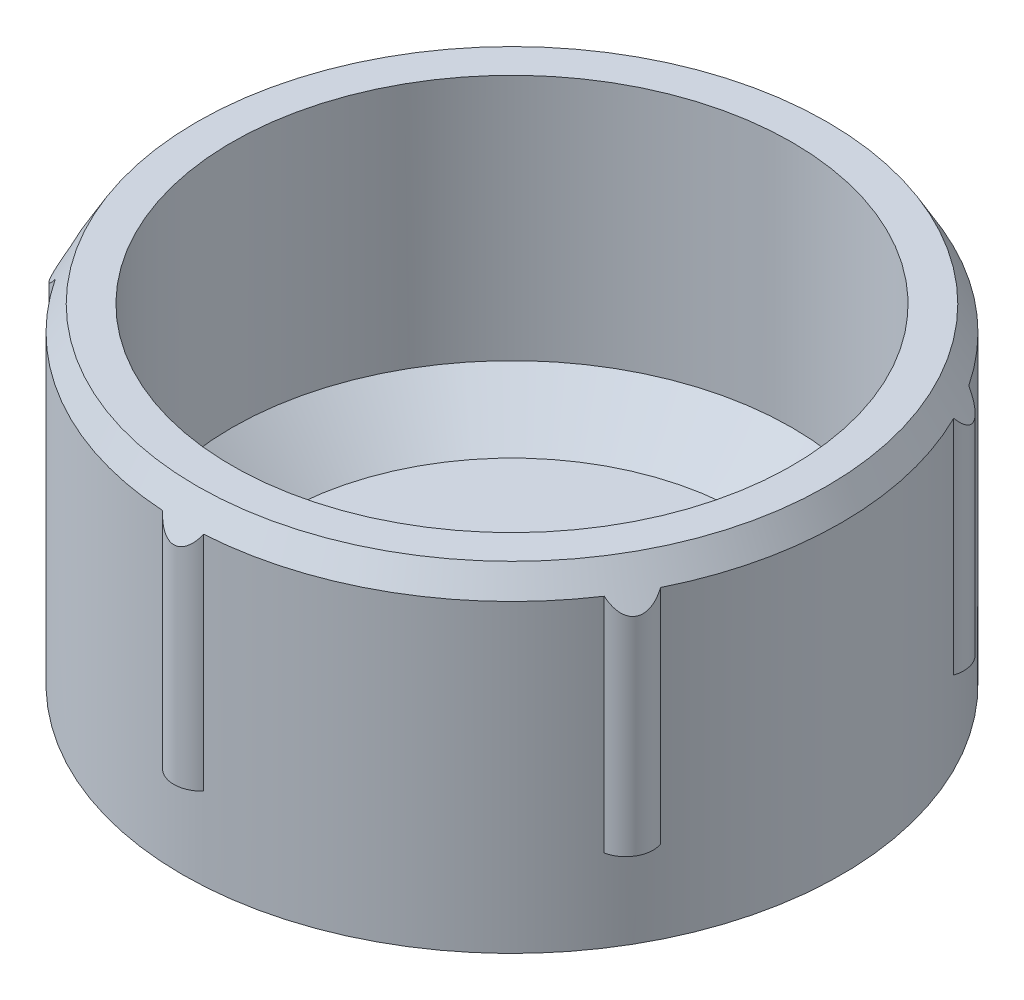
SolidWorks part; units mm, degrees
material "PET"
ref_plane "Front Plane" through (0, 0, 0) normal (0, 0, 1) x (1, 0, 0)
ref_plane "Top Plane" through (0, 0, 0) normal (0, 1, 0) x (1, 0, 0)
ref_plane "Right Plane" through (0, 0, 0) normal (1, 0, 0) x (0, 0, -1)
sketch "Sketch2" plane through (0, 0, 0) normal (0, 0, 1) x (1, 0, 0)
  line L0 (0, 0) -> (-20, 0)
  line L1 (-20, 0) -> (-20, 20)
  line L2 (-20, 20) -> (-17, 20)
  line L3 (-17, 20) -> (-17, 2)
  line L4 (-17, 2) -> (0, 2)
  line L5 (0, 2) -> (0, 0)
  line L6 (0, 0) -> (0, 22119.0408) construction
  dimension "D1" = 40
  dimension "D2" = 3
  dimension "D3" = 20
  dimension "D4" = 2
revolve "Revolve1" add sketch "Sketch2" angle 360 about L6
sketch "Sketch3" plane through (0, 20, 0) normal (0, 1, 0) x (1, 0, 0)
  arc A0 (-1.25, 19.9609) -> (1.25, 19.9609) centre (0, 18.8431) cw
  circle A1 centre (0, 0) radius 20 construction
  arc A2 (-1.25, 19.9609) -> (1.25, 19.9609) centre (0, 0) cw
  arc A3 (16.6616, 11.063) -> (17.9116, 8.8979) centre (0, 0) cw
  arc A4 (16.6616, 11.063) -> (17.9116, 8.8979) centre (16.3186, 9.4216) cw
  arc A5 (17.9116, -8.8979) -> (16.6616, -11.063) centre (0, 0) cw
  arc A6 (17.9116, -8.8979) -> (16.6616, -11.063) centre (16.3186, -9.4216) cw
  arc A7 (1.25, -19.9609) -> (-1.25, -19.9609) centre (0, 0) cw
  arc A8 (1.25, -19.9609) -> (-1.25, -19.9609) centre (0, -18.8431) cw
  arc A9 (-16.6616, -11.063) -> (-17.9116, -8.8979) centre (0, 0) cw
  arc A10 (-16.6616, -11.063) -> (-17.9116, -8.8979) centre (-16.3186, -9.4216) cw
  arc A11 (-17.9116, 8.8979) -> (-16.6616, 11.063) centre (0, 0) cw
  arc A12 (-17.9116, 8.8979) -> (-16.6616, 11.063) centre (-16.3186, 9.4216) cw
  point P24 (0, 0)
  dimension "D1" = 2.5
  dimension "D2" = 20.52
extrude "Boss-Extrude1" add sketch "Sketch3" against normal offset from surface (15 mm away) 5 up to face at (0, 0, -20)
ref_axis "Axis1" through (0, 20, 0) along (0, -1, 0)
sketch "Sketch4" plane through (0, 0, 0) normal (0, 0, 1) x (1, 0, 0)
  line L0 (-21, 16.7679) -> (-18.5566, 21)
  line L1 (-18.5566, 21) -> (-21, 21)
  line L2 (-21, 21) -> (-21, 16.7679)
  point P2 (-20, 20)
  dimension "D1" = 1
  dimension "D2" = 1
  dimension "D3" = 0.75
  dimension "D4" = 30
revolve "Cut-Revolve1" cut sketch "Sketch4" angle 360 about axis through (0, 20, 0) along (0, -1, 0)
sketch "Sketch5" plane through (0, 2, 0) normal (0, 1, 0) x (1, 0, 0)
  circle A0 centre (0, 9.5) radius 1.7
  circle A1 centre (8.2272, -4.75) radius 1.7
  circle A2 centre (-8.2272, -4.75) radius 1.7
  point P10 (0, 0)
  dimension "D3" = 3.4
  dimension "D1" = 9.5
  dimension "D2" = 3
extrude "Cut-Extrude1" cut sketch "Sketch5" against normal up to next
chamfer "Chamfer1" distance 3 angle 45 1 edges at (0, 2, -17)
equation "\"D2@Sketch3\"=(1.6in/2)+0.2mm"
